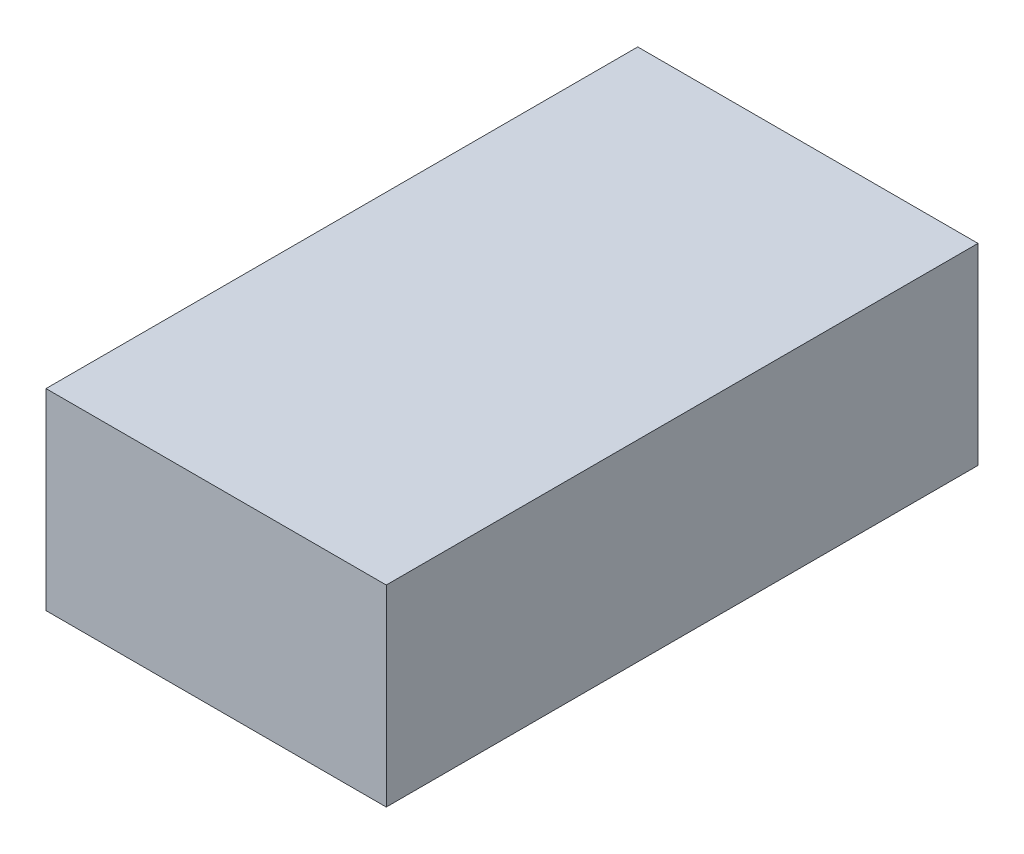
SolidWorks part; units mm, degrees
ref_plane "Front Plane" through (0, 0, 0) normal (0, 0, 1) x (1, 0, 0)
ref_plane "Top Plane" through (0, 0, 0) normal (0, 1, 0) x (1, 0, 0)
ref_plane "Right Plane" through (0, 0, 0) normal (1, 0, 0) x (0, 0, -1)
sketch "Sketch1" plane through (0, 0, 0) normal (0, 1, 0) x (1, 0, 0)
  line L2 (-11.5, 20) -> (11.5, 20)
  line L3 (-11.5, 20) -> (-11.5, -20)
  line L4 (-11.5, -20) -> (11.5, -20)
  line L5 (11.5, 20) -> (11.5, -20)
  line L6 (-11.5, 20) -> (11.5, -20) construction
  line L7 (-11.5, -20) -> (11.5, 20) construction
  point P1 (0, 0)
  dimension "D1" = 23
  dimension "D2" = 40
extrude "Boss-Extrude1" add sketch "Sketch1" along normal blind 13
